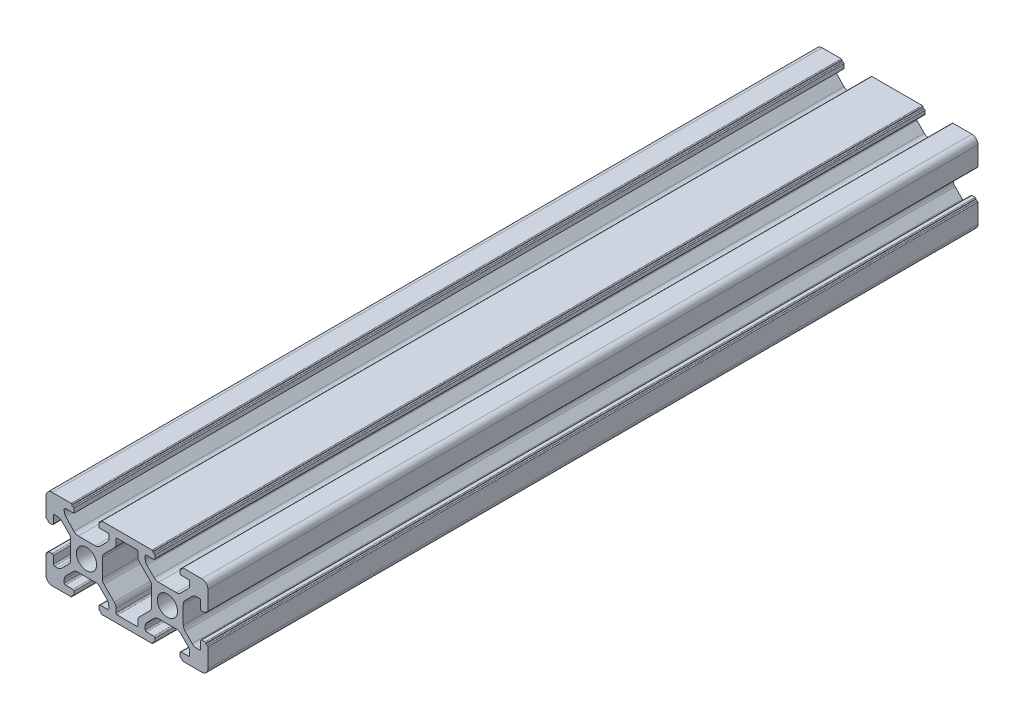
SolidWorks part; units mm, degrees
material "6063-O"
ref_plane "Front Plane" through (0, 0, 0) normal (0, 0, 1) x (1, 0, 0)
ref_plane "Top Plane" through (0, 0, 0) normal (0, 1, 0) x (1, 0, 0)
ref_plane "Right Plane" through (0, 0, 0) normal (1, 0, 0) x (0, 0, -1)
sketch "Sketch1" plane through (0, 0, 0) normal (0, 0, 1) x (1, 0, 0)
  line L0 (1.5, 0) -> (6.2, 0)
  line L1 (40, 1.5) -> (40, 6.2)
  line L2 (38.5, 20) -> (33.8, 20)
  line L3 (0, 18.5) -> (0, 13.8)
  line L4 (17.6, 1.8) -> (22.4, 1.8)
  line L5 (32.218, 13.9) -> (27.782, 13.9)
  line L6 (26.1, 12.218) -> (26.1, 7.782)
  line L7 (17.6, 18.2) -> (22.4, 18.2)
  line L8 (12.218, 13.9) -> (7.9864, 13.9)
  line L9 (6.1, 12.218) -> (6.1, 7.782)
  line L10 (7.782, 6.1) -> (12.218, 6.1)
  line L11 (13.9, 7.782) -> (13.9, 12.218)
  line L12 (27.782, 6.1) -> (32.218, 6.1)
  line L13 (33.9, 7.782) -> (33.9, 12.218)
  line L14 (26.7213, 14.3393) -> (24.9393, 16.1213)
  line L15 (33.2787, 14.3393) -> (35.0607, 16.1213)
  line L16 (34.3393, 13.2787) -> (36.1213, 15.0607)
  line L17 (25.6607, 6.7213) -> (23.1393, 4.2)
  line L18 (15.2, 1.8) -> (13.4, 1.8)
  line L19 (26.7213, 5.6607) -> (24.9393, 3.8787)
  line L20 (24.8, 1.8) -> (26.6, 1.8)
  line L21 (15.3, 18.2) -> (13.1, 18.2)
  line L22 (13.2787, 14.3393) -> (15.1607, 16.2213)
  line L23 (14.3393, 13.2787) -> (16.8607, 15.8)
  line L24 (5.6607, 6.7213) -> (3.8787, 4.9393)
  line L25 (6.7213, 5.6607) -> (4.9393, 3.8787)
  line L26 (6.897, 14.3689) -> (4.9106, 16.4674)
  line L27 (5.6607, 13.2787) -> (3.8787, 15.0607)
  line L28 (14.3393, 6.7213) -> (16.8607, 4.2)
  line L29 (13.2787, 5.6607) -> (15.0607, 3.8787)
  line L30 (24.8, 18.2) -> (26.6, 18.2)
  line L31 (25.6607, 13.2787) -> (23.1393, 15.8)
  line L32 (34.3393, 6.7213) -> (36.1213, 4.9393)
  line L33 (33.2787, 5.6607) -> (35.0607, 3.8787)
  line L34 (1.8, 15.2) -> (1.8, 13.4)
  line L35 (24.5, 2.1) -> (24.5, 2.818)
  line L36 (4.5, 2.1) -> (4.5, 2.818)
  line L37 (2.818, 4.5) -> (2.1, 4.5)
  line L38 (4.5, 17.9) -> (4.5, 17.4986)
  line L39 (2.818, 15.5) -> (2.1, 15.5)
  line L40 (15.6, 17.9) -> (15.6, 17.282)
  line L41 (15.5, 2.818) -> (15.5, 2.1)
  line L42 (38.2, 15.2) -> (38.2, 13.4)
  line L43 (35.5, 2.818) -> (35.5, 2.1)
  line L44 (37.182, 4.5) -> (37.9, 4.5)
  line L45 (35.5, 17.182) -> (35.5, 17.9)
  line L46 (37.182, 15.5) -> (37.9, 15.5)
  line L47 (17.3, 2.1) -> (17.3, 3.1393)
  line L48 (22.7, 2.1) -> (22.7, 3.1393)
  line L49 (17.3, 17.9) -> (17.3, 16.8607)
  line L50 (22.7, 17.9) -> (22.7, 16.8607)
  line L51 (24.5, 17.9) -> (24.5, 17.182)
  line L52 (6.9, 19.3) -> (6.9, 18.2)
  line L53 (13.1, 19.3) -> (13.1, 18.2)
  line L54 (6.9, 1.5) -> (6.9, 0.7)
  line L55 (13.1, 1.5) -> (13.1, 0.7)
  line L56 (13.8, 0) -> (26.2, 0)
  line L57 (6.6, 1.8) -> (4.8, 1.8)
  line L58 (6.9, 18.2) -> (4.8, 18.2)
  line L59 (6.2, 20) -> (1.5, 20)
  line L60 (39.3, 6.9) -> (38.5, 6.9)
  line L61 (39.3, 13.1) -> (38.5, 13.1)
  line L62 (1.5, 13.1) -> (0.7, 13.1)
  line L63 (1.5, 6.9) -> (0.7, 6.9)
  line L64 (0, 6.2) -> (0, 1.5)
  line L65 (1.8, 6.6) -> (1.8, 4.8)
  line L66 (38.2, 6.6) -> (38.2, 4.8)
  line L67 (40, 13.8) -> (40, 18.5)
  line L68 (33.1, 19.3) -> (33.1, 18.5)
  line L69 (26.9, 19.3) -> (26.9, 18.5)
  line L70 (26.9, 1.5) -> (26.9, 0.7)
  line L71 (33.1, 1.5) -> (33.1, 0.7)
  line L72 (33.8, 0) -> (38.5, 0)
  line L73 (33.4, 1.8) -> (35.2, 1.8)
  line L74 (26.2, 20) -> (13.8, 20)
  line L75 (33.4, 18.2) -> (35.2, 18.2)
  line L76 (6.7, 0.5) -> (6.6, 0.5)
  line L77 (6.4, 0.3) -> (6.4, 0.2)
  line L78 (13.3, 0.5) -> (13.4, 0.5)
  line L79 (13.6, 0.3) -> (13.6, 0.2)
  line L80 (26.7, 0.5) -> (26.6, 0.5)
  line L81 (26.4, 0.3) -> (26.4, 0.2)
  line L82 (33.3, 0.5) -> (33.4, 0.5)
  line L83 (33.6, 0.3) -> (33.6, 0.2)
  line L85 (6.4, 19.8) -> (6.4, 19.7)
  line L86 (6.6, 19.5) -> (6.7, 19.5)
  line L87 (13.6, 19.8) -> (13.6, 19.7)
  line L88 (13.4, 19.5) -> (13.3, 19.5)
  line L89 (26.4, 19.8) -> (26.4, 19.7)
  line L90 (26.6, 19.5) -> (26.7, 19.5)
  line L91 (33.6, 19.8) -> (33.6, 19.7)
  line L92 (33.4, 19.5) -> (33.3, 19.5)
  line L93 (0.5, 13.3) -> (0.5, 13.4)
  line L94 (0.3, 13.6) -> (0.2, 13.6)
  line L95 (0.5, 6.7) -> (0.5, 6.6)
  line L96 (0.3, 6.4) -> (0.2, 6.4)
  line L97 (39.5, 13.3) -> (39.5, 13.4)
  line L98 (39.7, 13.6) -> (39.8, 13.6)
  line L99 (39.5, 6.7) -> (39.5, 6.6)
  line L100 (39.7, 6.4) -> (39.8, 6.4)
  circle A0 centre (10, 10) radius 2.5
  circle A1 centre (30, 10) radius 2.5
  arc A2 (38.5, 0) -> (40, 1.5) centre (38.5, 1.5) ccw
  arc A3 (40, 18.5) -> (38.5, 20) centre (38.5, 18.5) ccw
  arc A4 (1.5, 0) -> (0, 1.5) centre (1.5, 1.5) cw
  arc A5 (1.5, 20) -> (0, 18.5) centre (1.5, 18.5) ccw
  arc A6 (26.7213, 5.6607) -> (27.782, 6.1) centre (27.782, 4.6) cw
  arc A7 (32.218, 6.1) -> (33.2787, 5.6607) centre (32.218, 4.6) cw
  arc A8 (33.9, 7.782) -> (34.3393, 6.7213) centre (35.4, 7.782) ccw
  arc A9 (33.2787, 14.3393) -> (32.218, 13.9) centre (32.218, 15.4) cw
  arc A10 (14.3393, 6.7213) -> (13.9, 7.782) centre (15.4, 7.782) cw
  arc A11 (14.3393, 13.2787) -> (13.9, 12.218) centre (15.4, 12.218) ccw
  arc A12 (25.6607, 6.7213) -> (26.1, 7.782) centre (24.6, 7.782) ccw
  arc A13 (26.1, 12.218) -> (25.6607, 13.2787) centre (24.6, 12.218) ccw
  arc A14 (27.782, 13.9) -> (26.7213, 14.3393) centre (27.782, 15.4) cw
  arc A15 (5.6607, 13.2787) -> (6.1, 12.218) centre (4.6, 12.218) cw
  arc A16 (5.6607, 6.7213) -> (6.1, 7.782) centre (4.6, 7.782) ccw
  arc A17 (13.2787, 5.6607) -> (12.218, 6.1) centre (12.218, 4.6) ccw
  arc A18 (6.7213, 5.6607) -> (7.782, 6.1) centre (7.782, 4.6) cw
  arc A19 (13.2787, 14.3393) -> (12.218, 13.9) centre (12.218, 15.4) cw
  arc A20 (6.897, 14.3689) -> (7.9864, 13.9) centre (7.9864, 15.4) ccw
  arc A21 (36.1213, 4.9393) -> (37.182, 4.5) centre (37.182, 6) ccw
  arc A22 (36.1213, 15.0607) -> (37.182, 15.5) centre (37.182, 14) cw
  arc A23 (35.0607, 16.1213) -> (35.5, 17.182) centre (34, 17.182) ccw
  arc A24 (24.5, 17.182) -> (24.9393, 16.1213) centre (26, 17.182) ccw
  arc A25 (22.7, 16.8607) -> (23.1393, 15.8) centre (24.2, 16.8607) ccw
  arc A26 (17.3, 16.8607) -> (16.8607, 15.8) centre (15.8, 16.8607) cw
  arc A27 (4.9106, 16.4674) -> (4.5, 17.4986) centre (6, 17.4986) cw
  arc A28 (15.6, 17.282) -> (15.1607, 16.2213) centre (14.1, 17.282) cw
  arc A29 (3.8787, 15.0607) -> (2.818, 15.5) centre (2.818, 14) ccw
  arc A30 (3.8787, 4.9393) -> (2.818, 4.5) centre (2.818, 6) cw
  arc A31 (4.9393, 3.8787) -> (4.5, 2.818) centre (6, 2.818) ccw
  arc A32 (35.0607, 3.8787) -> (35.5, 2.818) centre (34, 2.818) cw
  arc A33 (24.9393, 3.8787) -> (24.5, 2.818) centre (26, 2.818) ccw
  arc A34 (22.7, 3.1393) -> (23.1393, 4.2) centre (24.2, 3.1393) cw
  arc A35 (17.3, 3.1393) -> (16.8607, 4.2) centre (15.8, 3.1393) ccw
  arc A36 (15.5, 2.818) -> (15.0607, 3.8787) centre (14, 2.818) ccw
  arc A37 (1.8, 6.6) -> (1.5, 6.9) centre (1.5, 6.6) ccw
  arc A38 (1.8, 13.4) -> (1.5, 13.1) centre (1.5, 13.4) cw
  arc A39 (17.6, 18.2) -> (17.3, 17.9) centre (17.6, 17.9) ccw
  arc A40 (22.4, 1.8) -> (22.7, 2.1) centre (22.4, 2.1) ccw
  arc A41 (17.6, 1.8) -> (17.3, 2.1) centre (17.6, 2.1) cw
  arc A42 (15.2, 1.8) -> (15.5, 2.1) centre (15.2, 2.1) ccw
  arc A43 (6.6, 1.8) -> (6.9, 1.5) centre (6.6, 1.5) cw
  arc A44 (13.4, 1.8) -> (13.1, 1.5) centre (13.4, 1.5) ccw
  arc A45 (24.8, 1.8) -> (24.5, 2.1) centre (24.8, 2.1) cw
  arc A46 (35.2, 1.8) -> (35.5, 2.1) centre (35.2, 2.1) ccw
  arc A47 (26.6, 1.8) -> (26.9, 1.5) centre (26.6, 1.5) cw
  arc A48 (33.4, 1.8) -> (33.1, 1.5) centre (33.4, 1.5) ccw
  arc A49 (26.9, 18.5) -> (26.6, 18.2) centre (26.6, 18.5) cw
  arc A50 (33.1, 18.5) -> (33.4, 18.2) centre (33.4, 18.5) ccw
  arc A51 (37.9, 4.5) -> (38.2, 4.8) centre (37.9, 4.8) ccw
  arc A52 (38.5, 13.1) -> (38.2, 13.4) centre (38.5, 13.4) cw
  arc A53 (38.5, 6.9) -> (38.2, 6.6) centre (38.5, 6.6) ccw
  arc A54 (38.2, 15.2) -> (37.9, 15.5) centre (37.9, 15.2) ccw
  arc A55 (35.2, 18.2) -> (35.5, 17.9) centre (35.2, 17.9) cw
  arc A56 (24.8, 18.2) -> (24.5, 17.9) centre (24.8, 17.9) ccw
  arc A57 (22.4, 18.2) -> (22.7, 17.9) centre (22.4, 17.9) cw
  arc A58 (15.3, 18.2) -> (15.6, 17.9) centre (15.3, 17.9) cw
  arc A59 (4.5, 17.9) -> (4.8, 18.2) centre (4.8, 17.9) cw
  arc A60 (1.8, 15.2) -> (2.1, 15.5) centre (2.1, 15.2) cw
  arc A61 (1.8, 4.8) -> (2.1, 4.5) centre (2.1, 4.8) ccw
  arc A62 (4.5, 2.1) -> (4.8, 1.8) centre (4.8, 2.1) ccw
  arc A63 (34.3393, 13.2787) -> (33.9, 12.218) centre (35.4, 12.218) ccw
  arc A64 (6.4, 0.2) -> (6.2, 0) centre (6.2, 0.2) cw
  arc A65 (6.6, 0.5) -> (6.4, 0.3) centre (6.6, 0.3) ccw
  arc A66 (6.7, 0.5) -> (6.9, 0.7) centre (6.7, 0.7) ccw
  arc A67 (13.6, 0.2) -> (13.8, 0) centre (13.8, 0.2) ccw
  arc A68 (13.4, 0.5) -> (13.6, 0.3) centre (13.4, 0.3) cw
  arc A69 (13.3, 0.5) -> (13.1, 0.7) centre (13.3, 0.7) cw
  arc A70 (26.4, 0.2) -> (26.2, 0) centre (26.2, 0.2) cw
  arc A71 (26.6, 0.5) -> (26.4, 0.3) centre (26.6, 0.3) ccw
  arc A72 (26.7, 0.5) -> (26.9, 0.7) centre (26.7, 0.7) ccw
  arc A73 (33.6, 0.2) -> (33.8, 0) centre (33.8, 0.2) ccw
  arc A74 (33.4, 0.5) -> (33.6, 0.3) centre (33.4, 0.3) cw
  arc A75 (33.3, 0.5) -> (33.1, 0.7) centre (33.3, 0.7) cw
  arc A76 (39.8, 6.4) -> (40, 6.2) centre (39.8, 6.2) cw
  arc A77 (39.5, 6.6) -> (39.7, 6.4) centre (39.7, 6.6) ccw
  arc A78 (39.5, 6.7) -> (39.3, 6.9) centre (39.3, 6.7) ccw
  arc A79 (39.5, 13.3) -> (39.3, 13.1) centre (39.3, 13.3) cw
  arc A80 (39.5, 13.4) -> (39.7, 13.6) centre (39.7, 13.4) cw
  arc A81 (39.8, 13.6) -> (40, 13.8) centre (39.8, 13.8) ccw
  arc A82 (33.3, 19.5) -> (33.1, 19.3) centre (33.3, 19.3) ccw
  arc A83 (33.6, 19.7) -> (33.4, 19.5) centre (33.4, 19.7) cw
  arc A84 (33.6, 19.8) -> (33.8, 20) centre (33.8, 19.8) cw
  arc A85 (26.7, 19.5) -> (26.9, 19.3) centre (26.7, 19.3) cw
  arc A86 (26.4, 19.7) -> (26.6, 19.5) centre (26.6, 19.7) ccw
  arc A87 (26.4, 19.8) -> (26.2, 20) centre (26.2, 19.8) ccw
  arc A88 (0.2, 6.4) -> (0, 6.2) centre (0.2, 6.2) ccw
  arc A89 (0.5, 6.6) -> (0.3, 6.4) centre (0.3, 6.6) cw
  arc A90 (0.5, 6.7) -> (0.7, 6.9) centre (0.7, 6.7) cw
  arc A91 (13.3, 19.5) -> (13.1, 19.3) centre (13.3, 19.3) ccw
  arc A92 (13.6, 19.7) -> (13.4, 19.5) centre (13.4, 19.7) cw
  arc A93 (13.6, 19.8) -> (13.8, 20) centre (13.8, 19.8) cw
  arc A94 (6.2, 20) -> (6.4, 19.8) centre (6.2, 19.8) cw
  arc A95 (6.7, 19.5) -> (6.9, 19.3) centre (6.7, 19.3) cw
  arc A96 (6.4, 19.7) -> (6.6, 19.5) centre (6.6, 19.7) ccw
  arc A97 (0.5, 13.3) -> (0.7, 13.1) centre (0.7, 13.3) ccw
  arc A98 (0.2, 13.6) -> (0, 13.8) centre (0.2, 13.8) cw
  arc A99 (0.5, 13.4) -> (0.3, 13.6) centre (0.3, 13.4) ccw
  point P87 (0, 0)
  point P178 (1.8, 6.9)
  point P181 (1.8, 13.1)
  point P186 (22.7, 1.8)
  point P193 (6.9, 1.8)
  point P204 (33.1, 1.8)
  point P209 (33.1, 18.2)
  point P216 (38.2, 6.9)
  point P243 (6.9, 0.5)
  point P248 (13.6, 0.5)
  point P257 (26.9, 0.5)
extrude "Boss-Extrude2" add sketch "Sketch1" along normal blind 190.2 contours A57 L7 A39 L49 A26 L23 A11 L11 A10 L28 A35 L47 A41 L4 A40 L48 A34 L17 A12 L6 A13 L31 A25 L50 | A0 | A1 | L59 A5 L3 A98 L94 A99 L93 A97 L62 A38 L34 A60 L39 A29 L27 A15 L9 A16 L24 A30 L37 A61 L65 A37 L63 A90 L95 A89 L96 A88 L64 A4 L0 A64 L77 A65 L76 A66 L54 A43 L57 A62 L36 A31 L25 A18 L10 A17 L29 A36 L41 A42 L18 A44 L55 A69 L78 A68 L79 A67 L56 A70 L81 A71 L80 A72 L70 A47 L20 A45 L35 A33 L19 A6 L12 A7 L33 A32 L43 A46 L73 A48 L71 A75 L82 A74 L83 A73 L72 A2 L1 A76 L100 A77 L99 A78 L60 A53 L66 A51 L44 A21 L32 A8 L13 A63 L16 A22 L46 A54 L42 A52 L61 A79 L97 A80 L98 A81 L67 A3 L2 A84 L91 A83 L92 A82 L68 A50 L75 A55 L45 A23 L15 A9 L5 A14 L14 A24 L51 A56 L30 A49 L69 A85 L90 A86 L89 A87 L74 A93 L87 A92 L88 A91 L53 L21 A58 L40 A28 L22 A19 L8 A20 L26 A27 L38 A59 L58 L52 A95 L86 A96 L85 A94
